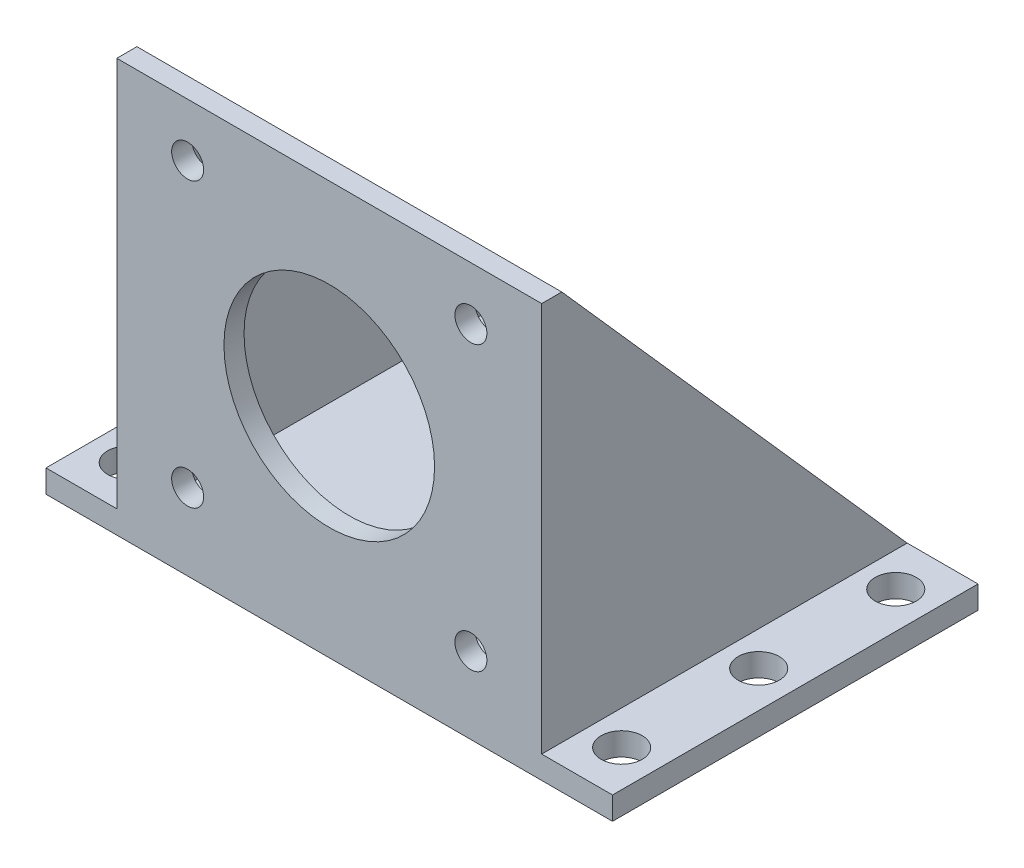
SolidWorks part; units mm, degrees
material "ABS"
ref_plane "Спереди" through (0, 0, 0) normal (0, 0, 1) x (1, 0, 0)
ref_plane "Сверху" through (0, 0, 0) normal (0, 1, 0) x (1, 0, 0)
ref_plane "Справа" through (0, 0, 0) normal (1, 0, 0) x (0, 0, -1)
sketch "Эскиз1" plane through (0, 0, 0) normal (0, 1, 0) x (1, 0, 0)
  line L0 (0, 20) -> (0, -20) construction
  line L1 (-31, 20) -> (31, 20)
  line L2 (-31, 20) -> (-31, -20)
  line L3 (-31, -20) -> (31, -20)
  line L4 (31, 20) -> (31, -20)
  line L5 (-31, 20) -> (31, -20) construction
  line L6 (-31, -20) -> (31, 20) construction
  circle A0 centre (-27, 0) radius 2.25
  circle A1 centre (27, 0) radius 2.25
  circle A2 centre (-27, 15) radius 2.25
  circle A3 centre (27, 15) radius 2.25
  circle A4 centre (-27, -15) radius 2.25
  circle A5 centre (27, -15) radius 2.25
  point P0 (0, 0)
  dimension "D3" = 4.5
  dimension "D6" = 15
  dimension "D8" = 15
  dimension "D1" = 40
  dimension "D2" = 62
  dimension "D4" = 54
  dimension "D5" = 2
  dimension "D7" = 2
extrude "Бобышка-Вытянуть1" add sketch "Эскиз1" along normal blind 2.5
sketch "Эскиз2" plane through (0, 0, 20) normal (0, 0, 1) x (1, 0, 0)
  line L0 (-31, 2.5) -> (31, 2.5) construction
  line L1 (-23.25, 2.5) -> (23.25, 2.5)
  line L2 (-23.25, 2.5) -> (-23.25, 45.2)
  line L3 (-23.25, 45.2) -> (23.25, 45.2)
  line L4 (23.25, 2.5) -> (23.25, 45.2)
  line L5 (-31, 0) -> (31, 0) construction
  line L6 (0, 23.875) -> (15.5, 39.375)
  circle A0 centre (0, 23.875) radius 11.525
  circle A1 centre (0, 23.875) radius 21.9203 construction
  circle A2 centre (15.5, 39.375) radius 1.75
  circle A3 centre (15.5, 8.375) radius 1.75
  circle A4 centre (-15.5, 8.375) radius 1.75
  circle A5 centre (-15.5, 39.375) radius 1.75
  point P6 (0, 45.2)
  point P24 (0, 23.875)
  dimension "D3" = 23.05
  dimension "D4" = 12.35
  dimension "D6" = 45
  dimension "D7" = 3.5
  dimension "D8" = 4
  dimension "D1" = 45.2
  dimension "D2" = 46.5
  dimension "D5" = 23.875
  dimension "D9" = 31
extrude "Бобышка-Вытянуть2" add sketch "Эскиз2" against normal blind 2.2
sketch "Эскиз3" plane through (-23.25, 0, 0) normal (-1, 0, 0) x (0, 0, 1)
  line L0 (-20, 2.5) -> (17.8, 45.2)
  line L1 (17.8, 45.2) -> (17.8, 2.5)
  line L2 (17.8, 2.5) -> (-20, 2.5)
extrude "Бобышка-Вытянуть3" add sketch "Эскиз3" against normal blind 1.6
sketch "Эскиз4" plane through (23.25, 0, 0) normal (1, 0, 0) x (0, 0, -1)
  line L3 (-17.8, 2.5) -> (20, 2.5)
  line L4 (20, 2.5) -> (-17.8, 45.2)
  line L5 (-17.8, 45.2) -> (-17.8, 2.5)
  line L6 (-17.8, 2.5) -> (20, 2.5)
  line L7 (20, 2.5) -> (-17.8, 45.2)
  line L8 (-17.8, 45.2) -> (-17.8, 2.5)
  dimension "D1" = 0
extrude "Бобышка-Вытянуть4" add sketch "Эскиз4" against normal blind 1.6
